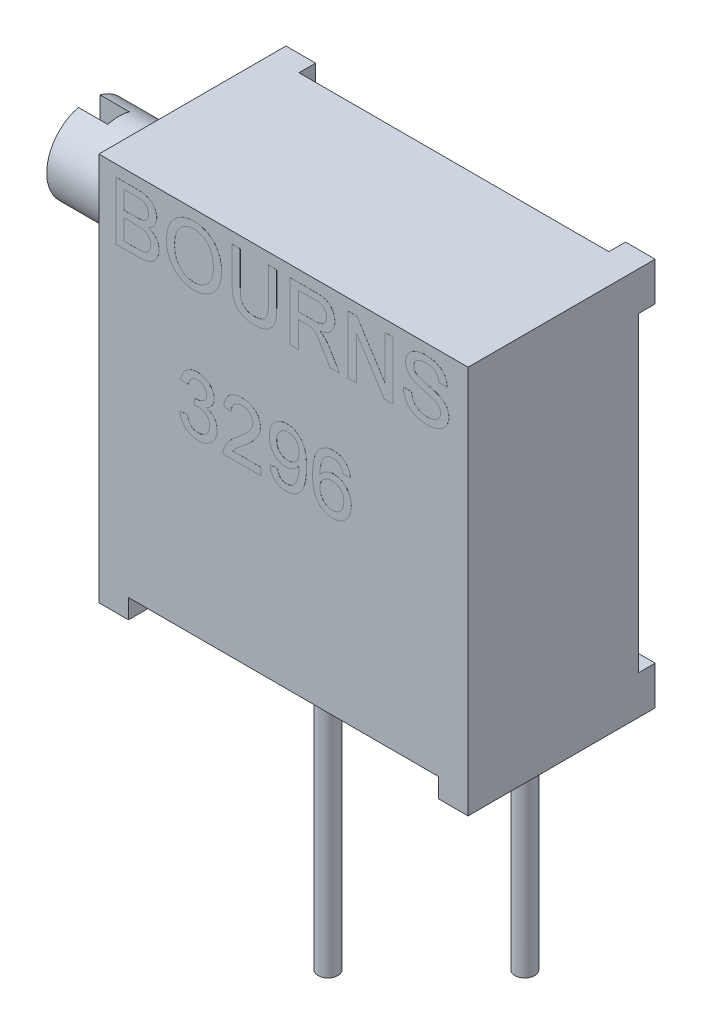
SolidWorks part; units mm, degrees
ref_plane "Plane1" through (0, 0, 0) normal (0, 0, 1) x (1, 0, 0)
ref_plane "Plane2" through (0, 0, 0) normal (0, 1, 0) x (1, 0, 0)
ref_plane "Plane3" through (0, 0, 0) normal (1, 0, 0) x (0, 0, -1)
sketch "Sketch1" plane through (0, 0, 0) normal (0, 0, 1) x (1, 0, 0)
  line L1 (-4.765, 0) -> (4.765, 0)
  line L2 (-4.765, 0) -> (-4.765, 10.03)
  line L3 (-4.765, 10.03) -> (4.765, 10.03)
  line L4 (4.765, 0) -> (4.765, 10.03)
  dimension "D1" = 9.53
  dimension "D2" = 10.03
extrude "Extrude1" add sketch "Sketch1" along normal blind 4.4
sketch "Sketch2" plane through (0, 0, 4.4) normal (0, 0, 1) x (1, 0, 0)
  line L0 (-4.765, 0) -> (4.765, 0) construction
  line L1 (-4, 0) -> (4, 0)
  line L2 (-4, 0) -> (-4, 0.5)
  line L3 (-4, 0.5) -> (4, 0.5)
  line L4 (4, 0) -> (4, 0.5)
  dimension "D1" = 8
  dimension "D2" = 0.5
extrude "Cut-Extrude1" cut sketch "Sketch2" against normal through all
sketch "Sketch3" plane through (0, 0, 0) normal (0, 0, -1) x (-1, 0, 0)
  line L1 (-4.765, 0) -> (-4, 0)
  line L2 (-4.765, 0) -> (-4.765, 1)
  line L3 (-4.765, 1) -> (-4, 1)
  line L4 (-4, 0) -> (-4, 1)
  line L5 (4.765, 0) -> (4, 0)
  line L6 (4.765, 0) -> (4.765, 1)
  line L7 (4.765, 1) -> (4, 1)
  line L8 (4, 0) -> (4, 1)
  line L9 (4.765, 10.03) -> (4, 10.03)
  line L10 (4.765, 10.03) -> (4.765, 9.03)
  line L11 (4.765, 9.03) -> (4, 9.03)
  line L12 (4, 10.03) -> (4, 9.03)
  line L13 (-4.765, 10.03) -> (-4, 10.03)
  line L14 (-4.765, 10.03) -> (-4.765, 9.03)
  line L15 (-4.765, 9.03) -> (-4, 9.03)
  line L16 (-4, 10.03) -> (-4, 9.03)
  dimension "D1" = 1
  dimension "D2" = 1
extrude "Extrude2" add sketch "Sketch3" along normal blind 0.43
sketch "Sketch4" plane through (0, 0.5, 0) normal (0, -1, 0) x (1, 0, 0)
  line L0 (0, 0) -> (0, 1.98) construction
  line L1 (-2.54, 1.98) -> (2.54, 1.98) construction
  line L2 (4.765, -0.43) -> (4, -0.43) construction
  circle A0 centre (2.54, 1.98) radius 0.255
  circle A1 centre (0, 1.98) radius 0.255
  circle A2 centre (-2.54, 1.98) radius 0.255
  dimension "D4" = 0.51
  dimension "D1" = 2.41
  dimension "D2" = 2.54
  dimension "D3" = 2.54
sketch "Sketch5" plane through (0, 10.03, 0) normal (0, 1, 0) x (-1, 0, 0)
  line L0 (-4.765, 4.4) -> (4.765, 4.4) construction
  line L1 (-4.765, 4.4) -> (-4.765, -0.43) construction
  circle A0 centre (-3.495, 3.13) radius 1.095
  dimension "D3" = 2.19
  dimension "D1" = 1.27
  dimension "D2" = 1.27
sketch "Sketch7" plane through (0, 0, 4.4) normal (0, 0, 1) x (1, 0, 0)
  text T0 "BOURNS\r\n   3296" font "Arial" height 1.5
extrude "Extrude5" add sketch "Sketch7" along normal blind 0.001
sketch "Sketch9" plane through (0, 0.5, 0) normal (0, -1, 0) x (1, 0, 0)
  line L0 (-2.54, 0.71) -> (2.54, 0.71) construction
  line L1 (0, 0) -> (0, 3.25) construction
  line L2 (-4, -0.43) -> (-4.765, -0.43) construction
  circle A0 centre (-2.54, 0.71) radius 0.255
  circle A1 centre (0, 3.25) radius 0.255
  circle A2 centre (2.54, 0.71) radius 0.255
  dimension "D5" = 0.51
  dimension "D1" = 1.14
  dimension "D2" = 2.54
  dimension "D3" = 2.54
  dimension "D4" = 2.54
extrude "Extrude7" add sketch "Sketch9" along normal blind 6.9
sketch "1" plane through (-4.765, 5.115, 6.5543) normal (-1, 0, 0) x (0, 0, 1)
  line L2 (-2.1543, 4.915) -> (-6.9843, 4.915) construction
  line L3 (-2.1543, 4.915) -> (-2.1543, -5.115) construction
  circle A0 centre (-3.4243, 3.645) radius 1.095
  dimension "D3" = 2.19
  dimension "D1" = 1.27
  dimension "D2" = 1.27
extrude "Extrude8" add sketch "1" along normal blind 1.52
sketch "2" plane through (-6.285, 5.115, 6.5543) normal (-1, 0, 0) x (0, 0, 1)
  line L0 (-3.4243, 3.645) -> (-3.4243, 1.593) construction
  line L1 (-3.1443, 1.593) -> (-3.7043, 1.593)
  line L2 (-3.1443, 1.593) -> (-3.1443, 5.9157)
  line L3 (-3.1443, 5.9157) -> (-3.7043, 5.9157)
  line L4 (-3.7043, 1.593) -> (-3.7043, 5.9157)
  dimension "D1" = 0.56
extrude "Cut-Extrude3" cut sketch "2" against normal blind 0.76
